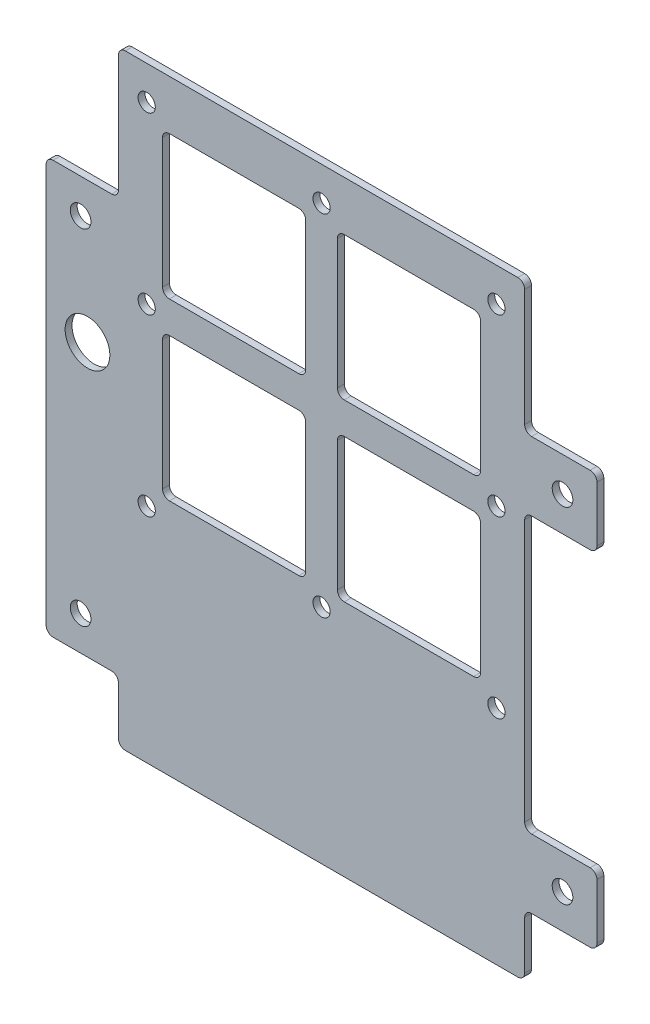
SolidWorks part; units mm, degrees
ref_plane "Спереди" through (0, 0, 0) normal (0, 0, 1) x (1, 0, 0)
ref_plane "Сверху" through (0, 0, 0) normal (0, 1, 0) x (1, 0, 0)
ref_plane "Справа" through (0, 0, 0) normal (1, 0, 0) x (0, 0, -1)
sketch "Model" plane through (0, 0, 0) normal (0, 0, 1) x (1, 0, 0)
  line L0 (-28.5, -69) -> (28.5, -69)
  line L1 (28.5, 19) -> (-28.5, 19)
  line L2 (-39, 0) -> (-30.5, 0)
  line L3 (-40, -5) -> (-40, -1)
  line L4 (-40, -5) -> (-40, -9)
  line L5 (-38, -60) -> (-31.5, -60)
  line L6 (-40, -55) -> (-40, -58)
  line L7 (-40, -55) -> (-40, -52)
  line L8 (-39, -60) -> (-30.5, -60)
  line L9 (-40, -55) -> (-40, -59)
  line L10 (-40, -55) -> (-40, -51)
  line L11 (-29.5, -61) -> (-29.5, -68)
  line L12 (38, 0) -> (31.5, 0)
  line L13 (38, -10) -> (31.5, -10)
  line L14 (40, -5) -> (40, -2)
  line L15 (40, -5) -> (40, -8)
  line L16 (38, -60) -> (31.5, -60)
  line L17 (38, -50) -> (31.5, -50)
  line L18 (40, -55) -> (40, -58)
  line L19 (40, -55) -> (40, -52)
  line L20 (38, -60) -> (31.5, -60)
  line L21 (38, -50) -> (31.5, -50)
  line L22 (40, -55) -> (40, -58)
  line L23 (40, -55) -> (40, -52)
  line L24 (29.5, 18) -> (29.5, 1)
  line L25 (39, 0) -> (30.5, 0)
  line L26 (39, -10) -> (30.5, -10)
  line L27 (40, -5) -> (40, -1)
  line L28 (40, -5) -> (40, -9)
  line L29 (38, -60) -> (31.5, -60)
  line L30 (38, -50) -> (31.5, -50)
  line L31 (40, -55) -> (40, -58)
  line L32 (40, -55) -> (40, -52)
  line L33 (39, -60) -> (30.5, -60)
  line L34 (39, -50) -> (30.5, -50)
  line L35 (40, -55) -> (40, -59)
  line L36 (40, -55) -> (40, -51)
  line L37 (29.5, -61) -> (29.5, -68)
  line L38 (-29.5, 18) -> (-29.5, 1)
  line L39 (29.5, -11) -> (29.5, -49)
  line L40 (0, 21) -> (0, -71) construction
  line L41 (-40, -9) -> (-40, -52)
  line L42 (-35, -5) -> (-35, -55) construction
  line L43 (-2.3, -8) -> (-2.3, 10.8)
  line L44 (-25.4, 14.1) -> (-25.4, -36.7) construction
  line L45 (-25.4, -36.7) -> (25.4, -36.7) construction
  line L46 (25.4, -36.7) -> (25.4, 14.1) construction
  line L47 (25.4, 14.1) -> (-25.4, 14.1) construction
  line L48 (-23.1, -8) -> (-23.1, 10.8)
  line L49 (-3.3, 11.8) -> (-22.1, 11.8)
  line L50 (-25.4, -11.3) -> (25.4, -11.3) construction
  line L51 (0, 14.1) -> (0, -36.7) construction
  line L52 (-3.3, -9) -> (-22.1, -9)
  line L53 (2.3, -8) -> (2.3, 10.8)
  line L54 (23.1, -8) -> (23.1, 10.8)
  line L55 (3.3, 11.8) -> (22.1, 11.8)
  line L56 (3.3, -9) -> (22.1, -9)
  line L57 (2.3, -8) -> (2.3, 10.8)
  line L58 (23.1, -8) -> (23.1, 10.8)
  line L59 (3.3, 11.8) -> (22.1, 11.8)
  line L60 (3.3, -9) -> (22.1, -9)
  line L61 (-2.3, -14.6) -> (-2.3, -33.4)
  line L62 (-23.1, -14.6) -> (-23.1, -33.4)
  line L63 (-3.3, -34.4) -> (-22.1, -34.4)
  line L64 (-3.3, -13.6) -> (-22.1, -13.6)
  line L65 (2.3, -14.6) -> (2.3, -33.4)
  line L66 (3.3, -34.4) -> (22.1, -34.4)
  line L67 (3.3, -13.6) -> (22.1, -13.6)
  line L68 (2.3, -14.6) -> (2.3, -33.4)
  line L69 (23.1, -14.6) -> (23.1, -33.4)
  line L70 (3.3, -34.4) -> (22.1, -34.4)
  line L71 (3.3, -13.6) -> (22.1, -13.6)
  line L72 (2.3, -14.6) -> (2.3, -33.4)
  line L73 (3.3, -34.4) -> (22.1, -34.4)
  line L74 (3.3, -13.6) -> (22.1, -13.6)
  line L75 (2.3, -14.6) -> (2.3, -33.4)
  line L76 (23.1, -14.6) -> (23.1, -33.4)
  line L77 (3.3, -34.4) -> (22.1, -34.4)
  line L78 (3.3, -13.6) -> (22.1, -13.6)
  line L79 (-34, -20.4) -> (-34, -15.15) construction
  line L80 (-34, -20.4) -> (-34, -25.65) construction
  line L81 (-34, -20.4) -> (-39.25, -20.4) construction
  line L82 (-34, -20.4) -> (-28.75, -20.4) construction
  circle A0 centre (-35, -5) radius 1.5
  circle A1 centre (-35, -55) radius 1.5
  circle A2 centre (-35, -55) radius 1.5
  circle A3 centre (35, -5) radius 1.5
  circle A4 centre (35, -55) radius 1.5
  circle A5 centre (35, -55) radius 1.5
  circle A6 centre (35, -5) radius 1.5
  circle A7 centre (35, -55) radius 1.5
  circle A8 centre (35, -55) radius 1.5
  arc A9 (-29.5, -68) -> (-28.5, -69) centre (-28.5, -68) ccw
  arc A10 (28.5, -69) -> (29.5, -68) centre (28.5, -68) ccw
  arc A11 (-28.5, 19) -> (-29.5, 18) centre (-28.5, 18) ccw
  arc A12 (29.5, 18) -> (28.5, 19) centre (28.5, 18) ccw
  arc A13 (40, -1) -> (39, 0) centre (39, -1) ccw
  arc A14 (39, -10) -> (40, -9) centre (39, -9) ccw
  arc A15 (40, -51) -> (39, -50) centre (39, -51) ccw
  arc A16 (39, -60) -> (40, -59) centre (39, -59) ccw
  arc A17 (-40, -59) -> (-39, -60) centre (-39, -59) ccw
  arc A18 (-39, 0) -> (-40, -1) centre (-39, -1) ccw
  arc A19 (-30.5, 0) -> (-29.5, 1) centre (-30.5, 1) ccw
  arc A20 (29.5, 1) -> (30.5, 0) centre (30.5, 1) ccw
  arc A21 (30.5, -10) -> (29.5, -11) centre (30.5, -11) ccw
  arc A22 (29.5, -49) -> (30.5, -50) centre (30.5, -49) ccw
  arc A23 (-29.5, -61) -> (-30.5, -60) centre (-30.5, -61) ccw
  arc A24 (30.5, -60) -> (29.5, -61) centre (30.5, -61) ccw
  circle A25 centre (-34, -20.4) radius 3.25
  arc A26 (-3.3, -9) -> (-2.3, -8) centre (-3.3, -8) ccw
  arc A27 (-2.3, 10.8) -> (-3.3, 11.8) centre (-3.3, 10.8) ccw
  circle A28 centre (25.4, -36.7) radius 1.25
  circle A29 centre (0, -36.7) radius 1.25
  circle A30 centre (25.4, 14.1) radius 1.25
  circle A31 centre (0, 14.1) radius 1.25
  circle A32 centre (-25.4, -11.3) radius 1.25
  circle A33 centre (-25.4, -36.7) radius 1.25
  circle A34 centre (-25.4, 14.1) radius 1.25
  circle A35 centre (25.4, -11.3) radius 1.25
  arc A36 (-22.1, 11.8) -> (-23.1, 10.8) centre (-22.1, 10.8) ccw
  arc A37 (-23.1, -8) -> (-22.1, -9) centre (-22.1, -8) ccw
  arc A38 (2.3, -8) -> (3.3, -9) centre (3.3, -8) ccw
  arc A39 (3.3, 11.8) -> (2.3, 10.8) centre (3.3, 10.8) ccw
  arc A40 (23.1, 10.8) -> (22.1, 11.8) centre (22.1, 10.8) ccw
  arc A41 (22.1, -9) -> (23.1, -8) centre (22.1, -8) ccw
  arc A42 (2.3, -8) -> (3.3, -9) centre (3.3, -8) ccw
  arc A43 (3.3, 11.8) -> (2.3, 10.8) centre (3.3, 10.8) ccw
  arc A44 (23.1, 10.8) -> (22.1, 11.8) centre (22.1, 10.8) ccw
  arc A45 (22.1, -9) -> (23.1, -8) centre (22.1, -8) ccw
  arc A46 (-2.3, -14.6) -> (-3.3, -13.6) centre (-3.3, -14.6) ccw
  arc A47 (-3.3, -34.4) -> (-2.3, -33.4) centre (-3.3, -33.4) ccw
  arc A48 (-23.1, -33.4) -> (-22.1, -34.4) centre (-22.1, -33.4) ccw
  arc A49 (-22.1, -13.6) -> (-23.1, -14.6) centre (-22.1, -14.6) ccw
  arc A50 (3.3, -13.6) -> (2.3, -14.6) centre (3.3, -14.6) ccw
  arc A51 (2.3, -33.4) -> (3.3, -34.4) centre (3.3, -33.4) ccw
  arc A52 (22.1, -34.4) -> (23.1, -33.4) centre (22.1, -33.4) ccw
  arc A53 (23.1, -14.6) -> (22.1, -13.6) centre (22.1, -14.6) ccw
  arc A54 (3.3, -13.6) -> (2.3, -14.6) centre (3.3, -14.6) ccw
  arc A55 (2.3, -33.4) -> (3.3, -34.4) centre (3.3, -33.4) ccw
  arc A56 (22.1, -34.4) -> (23.1, -33.4) centre (22.1, -33.4) ccw
  arc A57 (23.1, -14.6) -> (22.1, -13.6) centre (22.1, -14.6) ccw
  arc A58 (3.3, -13.6) -> (2.3, -14.6) centre (3.3, -14.6) ccw
  arc A59 (2.3, -33.4) -> (3.3, -34.4) centre (3.3, -33.4) ccw
  arc A60 (22.1, -34.4) -> (23.1, -33.4) centre (22.1, -33.4) ccw
  arc A61 (23.1, -14.6) -> (22.1, -13.6) centre (22.1, -14.6) ccw
  arc A62 (3.3, -13.6) -> (2.3, -14.6) centre (3.3, -14.6) ccw
  arc A63 (2.3, -33.4) -> (3.3, -34.4) centre (3.3, -33.4) ccw
  arc A64 (22.1, -34.4) -> (23.1, -33.4) centre (22.1, -33.4) ccw
  arc A65 (23.1, -14.6) -> (22.1, -13.6) centre (22.1, -14.6) ccw
extrude "Бобышка-Вытянуть1" add sketch "Model" along normal blind 1 contours A24 L33 L16 A16 L35 L18 L19 L36 A15 L34 L17 A22 L39 A21 L26 L13 A14 L28 L15 L14 L27 A13 L25 L12 A20 L24 A12 L1 A11 L38 A19 L2 A18 L3 L4 L41 L10 L7 L6 L9 A17 L8 L5 A23 L11 A9
